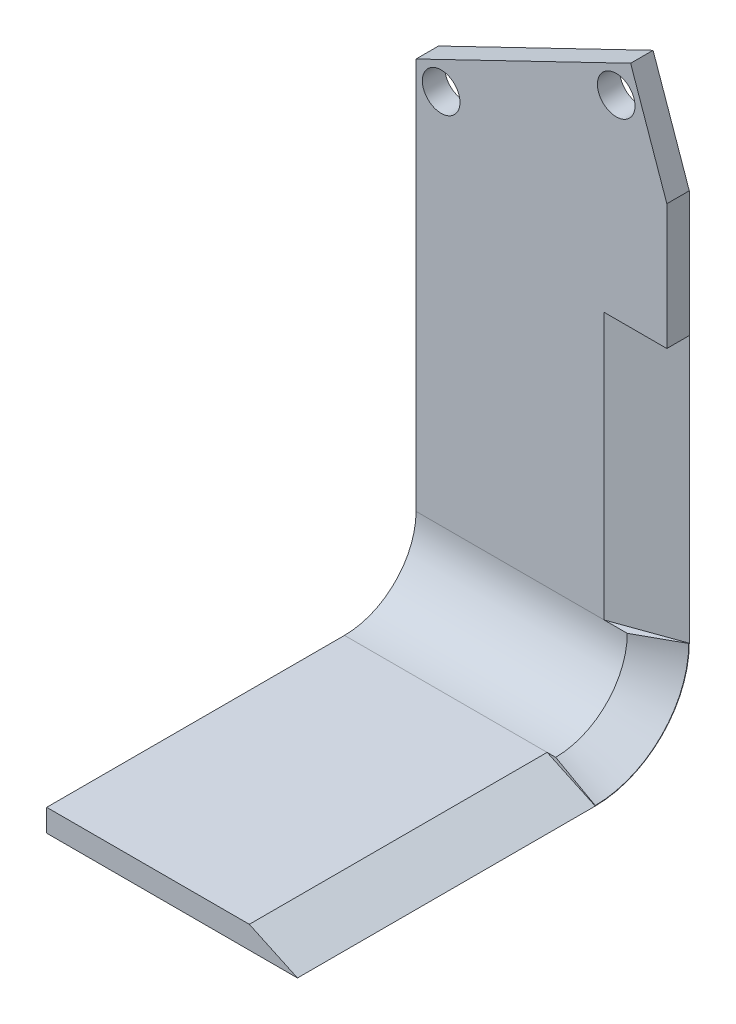
SolidWorks part; units mm, degrees
ref_plane "Front Plane" through (0, 0, 0) normal (0, 0, 1) x (1, 0, 0)
ref_plane "Top Plane" through (0, 0, 0) normal (0, 1, 0) x (1, 0, 0)
ref_plane "Right Plane" through (0, 0, 0) normal (1, 0, 0) x (0, 0, -1)
sketch "Sketch1" plane through (0, 0, 0) normal (1, 0, 0) x (0, 0, -1)
  line L0 (-43.0588, 0) -> (51.9412, 0)
  line L1 (81.9412, 30) -> (81.9412, 155)
  line L2 (-43.0588, 7.16) -> (51.9412, 7.16)
  line L3 (74.7812, 30) -> (74.7812, 155)
  line L4 (-43.0588, 0) -> (-43.0588, 7.16)
  line L5 (74.7812, 155) -> (81.9412, 155)
  arc A0 (51.9412, 0) -> (81.9412, 30) centre (51.9412, 30) ccw
  arc A1 (51.9412, 7.16) -> (74.7812, 30) centre (51.9412, 30) ccw
  point P6 (81.9412, 0)
  dimension "D3" = 30
  dimension "D1" = 125
  dimension "D2" = 155
  dimension "D4" = 7.16
extrude "Boss-Extrude1" add sketch "Sketch1" along normal blind 80
ref_plane "Plane1" through (0, 0, -74.7812) normal (0, 0, 1) x (1, 0, 0)
sketch "Sketch2" plane through (0, 0, -74.7812) normal (0, 0, 1) x (1, 0, 0)
  line L0 (0, 155) -> (68.4437, 188.0371)
  line L1 (68.4437, 188.0371) -> (80, 155)
  line L2 (80, 155) -> (0, 155)
  dimension "D1" = 76
  dimension "D2" = 35
extrude "Boss-Extrude2" add sketch "Sketch2" against normal blind 7.16
sketch "Sketch3" plane through (0, 0, -74.7812) normal (0, 0, 1) x (1, 0, 0)
  line L0 (80, 155) -> (68.4437, 188.0371) construction
  line L1 (68.4437, 188.0371) -> (0, 155) construction
  line L2 (0, 155) -> (0, 30) construction
  circle A0 centre (63.8512, 176.9371) radius 6
  circle A1 centre (8, 149.9783) radius 6
  dimension "D1" = 12
  dimension "D4" = 12
  dimension "D2" = 8
  dimension "D3" = 8
  dimension "D5" = 8
  dimension "D6" = 8
  dimension "D7" = 62.0172
  dimension "D8" = 62.0172
extrude "Cut-Extrude1" cut sketch "Sketch3" against normal blind 7.16 contours A0 | A1
sketch "Sketch4" plane through (0, 0, -74.7812) normal (0, 0, 1) x (1, 0, 0)
  line L0 (80, 155) -> (80, 115) construction
  line L1 (80, 155) -> (80, 30) construction
  dimension "D1" = 40
sketch "Sketch6" plane through (0, 0, 43.0588) normal (0, 0, 1) x (1, 0, 0)
  line L0 (80, 0) -> (64.6453, 7.16)
  line L1 (80, 7.16) -> (0, 7.16) construction
  line L2 (64.6453, 7.16) -> (80, 7.16)
  line L3 (80, 7.16) -> (80, 0)
  line L4 (80, 0) -> (0, 0) construction
  dimension "D1" = 25
extrude "Cut-Extrude6" cut sketch "Sketch6" against normal blind 95
sketch "Sketch8" plane through (80, 0, 0) normal (1, 0, 0) x (0, 0, -1)
  line L0 (74.7812, 115) -> (81.9412, 115)
  line L1 (81.9412, 30) -> (81.9412, 155) construction
sketch "Sketch9" plane through (0, 0, -74.7812) normal (0, 0, 1) x (1, 0, 0)
  line L0 (80, 115) -> (0, 115)
  line L1 (0, 155) -> (0, 30) construction
ref_plane "Plane2" through (0, 115, 0) normal (0, -1, 0) x (-1, 0, 0)
sketch "Sketch10" plane through (0, 115, 0) normal (0, -1, 0) x (-1, 0, 0)
  line L5 (-80, 81.9412) -> (-60, 74.7812)
  line L6 (-80, 74.7812) -> (-80, 81.9412) construction
  line L7 (-80, 74.7812) -> (0, 74.7812) construction
  line L8 (-60, 74.7812) -> (-80, 74.7812)
  line L9 (-80, 74.7812) -> (-80, 81.9412)
  dimension "D1" = 20
extrude "Cut-Extrude7" cut sketch "Sketch10" along normal blind 85
sketch "Sketch11" plane through (80, 0, 0) normal (1, 0, 0) x (0, 0, -1)
  line L2 (81.9412, 30) -> (74.7812, 30)
  line L3 (51.9412, 7.16) -> (51.9412, 0)
  line L4 (81.9412, 30) -> (74.7812, 30)
  line L5 (51.9412, 7.16) -> (51.9412, 0)
  arc A2 (51.9412, 7.16) -> (74.7812, 30) centre (51.9412, 30) ccw
  arc A3 (51.9412, 0) -> (81.9412, 30) centre (51.9412, 30) ccw
  arc A4 (51.9412, 7.16) -> (74.7812, 30) centre (51.9412, 30) ccw
  arc A5 (51.9412, 0) -> (81.9412, 30) centre (51.9412, 30) ccw
  dimension "D1" = 0
chamfer "Chamfer3" distance 7 angle 61 1 edges at (80, 13.8497, -68.0916)
scale "Scale1" scale about centroid uniform scaling yes scale factor 0.714782
scale "Scale2" scale about centroid uniform scaling yes scale factor 0.5
scale "Scale3" scale about centroid uniform scaling yes scale factor 1.5
